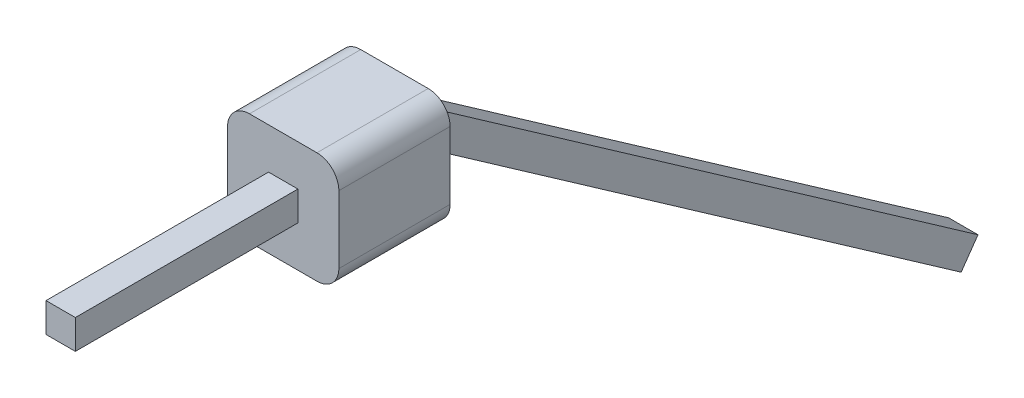
SolidWorks part; units mm, degrees
ref_plane "前视基准面" through (0, 0, 0) normal (0, 0, 1) x (1, 0, 0)
ref_plane "上视基准面" through (0, 0, 0) normal (0, 1, 0) x (1, 0, 0)
ref_plane "右视基准面" through (0, 0, 0) normal (1, 0, 0) x (0, 0, -1)
sketch "草图1" plane through (0, 0, 0) normal (0, 0, 1) x (1, 0, 0)
  line L0 (0, 5.3599) -> (0, -8.0108) construction
  line L1 (-1.27, -0.0191) -> (1.27, -0.0191)
  line L2 (-1.27, -0.0191) -> (-1.27, -2.5591)
  line L3 (-1.27, -2.5591) -> (1.27, -2.5591)
  line L4 (1.27, -0.0191) -> (1.27, -2.5591)
  dimension "D1" = 2.54
  dimension "D2" = 2.54
extrude "拉伸1" add sketch "草图1" along normal blind 2.54
ref_plane "基准面1" through (0, 0, 7.62) normal (0, 0, -1) x (-1, 0, 0)
sketch "草图2" plane through (0, 0, 7.62) normal (0, 0, -1) x (-1, 0, 0)
  line L0 (-1.27, -1.2891) -> (1.27, -1.2891) construction
  line L1 (-1.27, -2.5591) -> (-1.27, -0.0191) construction
  line L2 (1.27, -0.0191) -> (1.27, -2.5591) construction
  line L3 (0, 1.9407) -> (0, -4.2425) construction
  line L5 (-0.335, -0.9541) -> (0.335, -0.9541)
  line L6 (-0.335, -0.9541) -> (-0.335, -1.6241)
  line L7 (-0.335, -1.6241) -> (0.335, -1.6241)
  line L8 (0.335, -0.9541) -> (0.335, -1.6241)
  dimension "D1" = 0.67
  dimension "D2" = 0.67
sketch "草图3" plane through (0, 0, 0) normal (1, 0, 0) x (0, 0, -1)
  line L0 (0.5, -1.2991) -> (-7.62, -1.2991)
  line L1 (-7.62, 1.9407) -> (-7.62, -4.2425) construction
  line L2 (0.5, -1.2991) -> (12.7873, -9.9027)
  line L8 (-2.54, -0.0191) -> (0, -0.0191) construction
  line L9 (0, -2.5591) -> (0, -0.0191) construction
  point P11 (2.54, -1.2991)
  dimension "D5" = 15
  dimension "D1" = 7.62
  dimension "D2" = 8.12
  dimension "D3" = 35
  dimension "D4" = 1.28
sweep "扫描1" add profiles "草图2" path "草图3"
fillet "圆角1" radius 0.5 4 edges at (1.27, -0.0191, 1.27) (1.27, -2.5591, 1.27) (-1.27, -2.5591, 1.27) (-1.27, -0.0191, 1.27)
